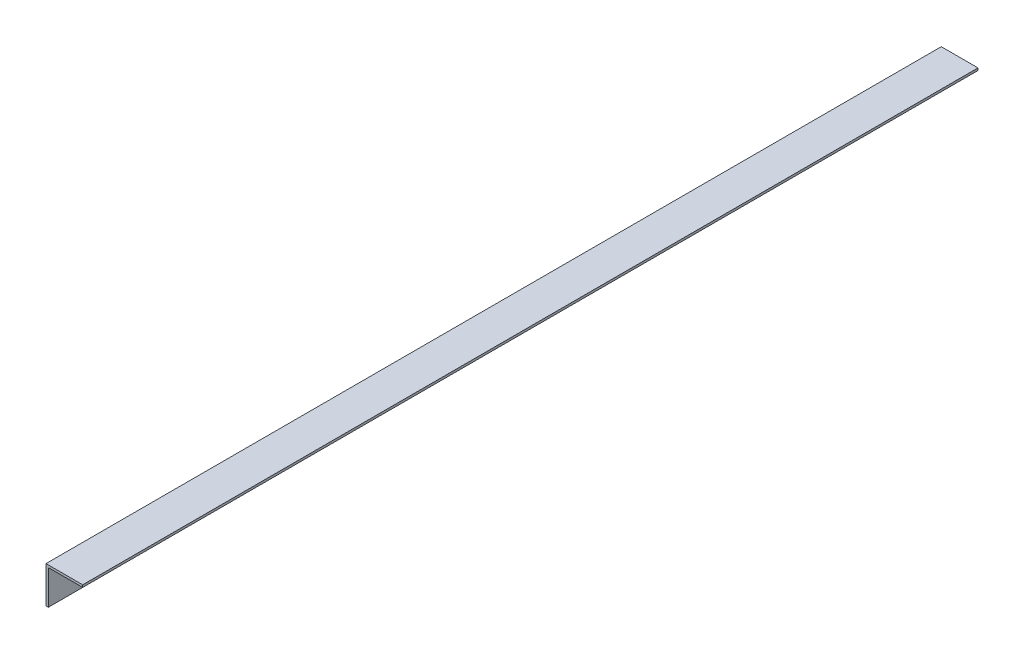
SolidWorks part; units mm, degrees
ref_plane "Front Plane" through (0, 0, 0) normal (0, 0, 1) x (1, 0, 0)
ref_plane "Top Plane" through (0, 0, 0) normal (0, 1, 0) x (1, 0, 0)
ref_plane "Right Plane" through (0, 0, 0) normal (1, 0, 0) x (0, 0, -1)
other "Configuration Table"
sketch "Sketch1" plane through (0, 0, 0) normal (0, 0, 1) x (1, 0, 0)
  line L0 (38, 1122) -> (40, 1122)
  line L1 (40, 1122) -> (40, 1152)
  line L2 (40, 1152) -> (70, 1152)
  line L3 (70, 1152) -> (70, 1154)
  line L4 (70, 1154) -> (38, 1154)
  line L5 (38, 1154) -> (38, 1122)
extrude "PRESS_uc_rafi_kosebent_sol_1" add sketch "Sketch1" against normal blind 780 from offset 20 separate body
